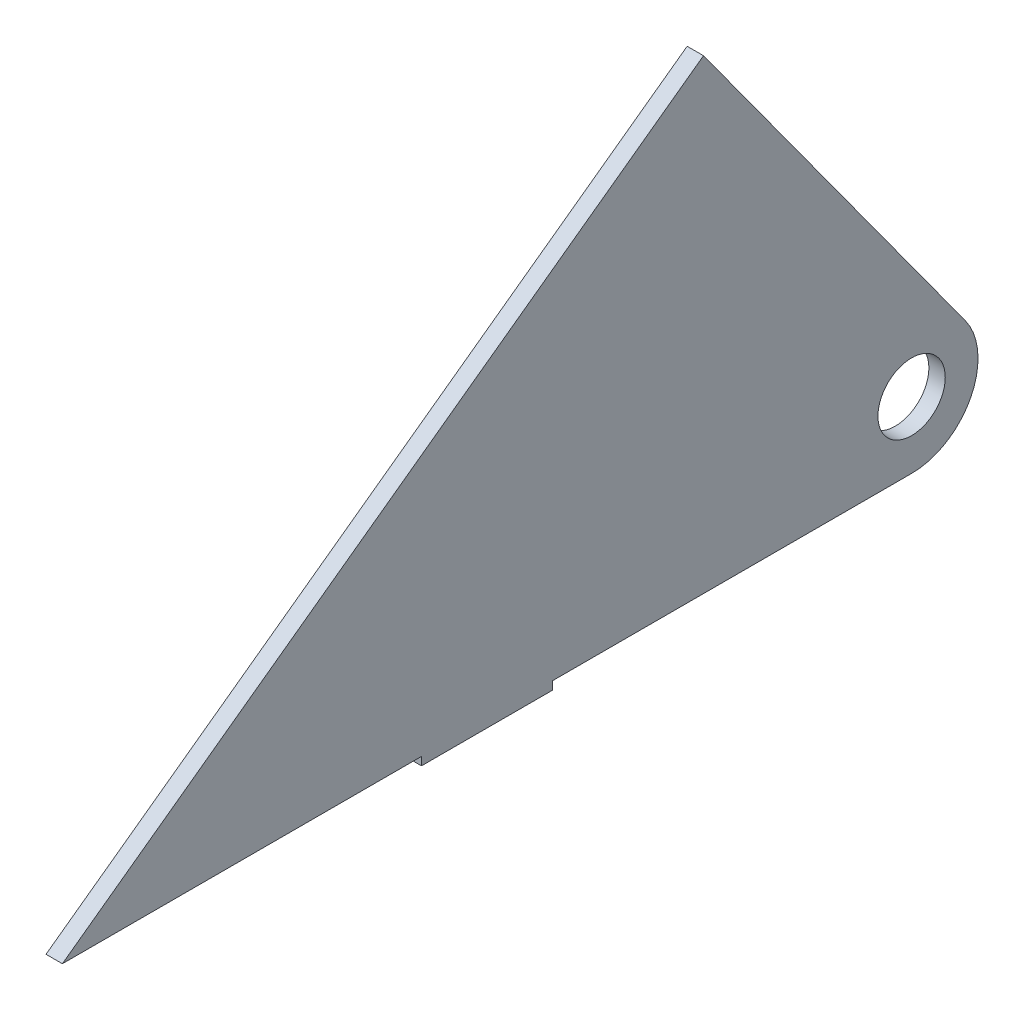
SolidWorks part; units mm, degrees
material "AISI 4130 Steel, annealed at 865C"
ref_plane "X-Y Datum" through (0, 0, 0) normal (0, 0, 1) x (1, 0, 0)
ref_plane "X-Z Datum" through (0, 0, 0) normal (0, 1, 0) x (1, 0, 0)
ref_plane "Y-Z Datum" through (0, 0, 0) normal (1, 0, 0) x (0, 0, -1)
sketch "Sketch1" plane through (0, 0, 0) normal (1, 0, 0) x (0, 0, -1)
  line L0 (0, 0) -> (-76.2, 0) construction
  line L4 (-20.1714, 38.718) -> (-82.3246, -6.4389)
  line L5 (-20.1714, 38.718) -> (5.2092, 3.7847)
  line L6 (0, -6.4389) -> (-82.3246, -6.4389)
  line L7 (-20.1714, 38.718) -> (-3.251, 15.4291) construction
  line L8 (-47.5123, -7.2327) -> (-34.8123, -7.2327)
  line L9 (-47.5123, -7.2327) -> (-47.5123, -5.6452)
  line L10 (-47.5123, -5.6452) -> (-34.8123, -5.6452)
  line L11 (-34.8123, -7.2327) -> (-34.8123, -5.6452)
  line L12 (-47.5123, -7.2327) -> (-34.8123, -5.6452) construction
  line L13 (-47.5123, -5.6452) -> (-34.8123, -7.2327) construction
  line L18 (-14.8015, 32.6774) -> (-7.3366, 22.4029)
  line L19 (-14.8015, 32.6774) -> (-16.0858, 31.7443)
  line L20 (-7.3366, 22.4029) -> (-8.6209, 21.4698)
  line L21 (-16.0858, 31.7443) -> (-8.6209, 21.4698)
  line L22 (-14.8015, 32.6774) -> (-8.6209, 21.4698) construction
  line L23 (-7.3366, 22.4029) -> (-16.0858, 31.7443) construction
  line L24 (-11.7112, 27.0736) -> (-4.1663, 32.5553) construction
  circle A0 centre (0, 0) radius 3.2639
  arc A1 (-0.5794, -6.4128) -> (-0.5794, 6.4128) centre (0, 0) ccw
  point P12 (-11.7112, 27.0736)
  point P13 (-41.1623, -6.4389)
  dimension "D1" = 6.5278
  dimension "D2" = 3.175
  dimension "D4" = 43.18
  dimension "D3" = 76.2
  dimension "D5" = 36
  dimension "D6" = 12.7
  dimension "D7" = 1.5875
  dimension "D8" = 28.7867
  dimension "D9" = 1.5875
  dimension "D10" = 12.7
extrude "Boss-Extrude1" add sketch "Sketch1" along normal mid plane 1.5875
